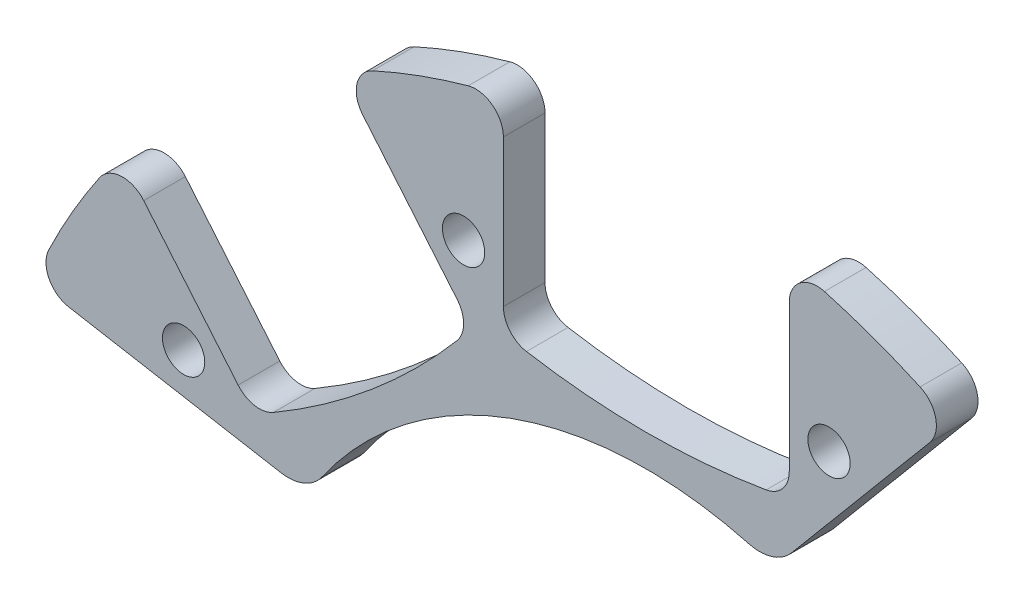
SolidWorks part; units mm, degrees
material "ﾎﾟﾘｶｰﾎﾞﾈｰﾄ(PC)高粘度"
ref_plane "正面" through (0, 0, 0) normal (0, 0, 1) x (1, 0, 0)
ref_plane "平面" through (0, 0, 0) normal (0, 1, 0) x (1, 0, 0)
ref_plane "右側面" through (0, 0, 0) normal (1, 0, 0) x (0, 0, -1)
sketch "ｽｹｯﾁ1" plane through (0, 0, 0) normal (0, 0, 1) x (1, 0, 0)
  circle A0 centre (0, 0) radius 47.75
  dimension "D1" = 95.5
extrude "ﾎﾞｽ - 押し出し1" add sketch "ｽｹｯﾁ1" along normal blind 3
sketch "ｽｹｯﾁ2" plane through (0, 0, 3) normal (0, 0, 1) x (1, 0, 0)
  line L0 (-10.3, 46.6259) -> (-10.3, 42.705)
  line L1 (10.3, 46.6259) -> (10.3, 42.705)
  line L2 (0, 47.75) -> (0, -47.75) construction
  line L3 (-10.3, 39.655) -> (-10.3, 31.8257)
  line L4 (12.9, 39.655) -> (10.3, 39.655)
  line L5 (12.9, 39.655) -> (12.9, 42.705)
  line L6 (12.9, 42.705) -> (10.3, 42.705)
  line L7 (-12.9, 39.655) -> (-12.9, 42.705)
  line L8 (12.9, 39.655) -> (-12.9, 42.705) construction
  line L9 (12.9, 42.705) -> (-12.9, 39.655) construction
  line L10 (-10.3, 39.655) -> (-12.9, 39.655)
  line L11 (-10.3, 42.705) -> (-12.9, 42.705)
  line L12 (10.3, 39.655) -> (10.3, 31.8257)
  line L13 (0, 30.78) -> (0, 41.18) construction
  line L14 (17.5995, 36.9982) -> (12.5669, 31.0006)
  line L15 (17.5995, 36.9982) -> (15.6078, 38.6695)
  line L16 (15.6078, 38.6695) -> (17.5683, 41.0059)
  line L17 (19.56, 39.3346) -> (17.5683, 41.0059)
  line L18 (22.0803, 42.3382) -> (19.56, 39.3346)
  line L19 (37.8608, 29.0968) -> (35.3405, 26.0932)
  line L20 (37.3322, 24.422) -> (35.3405, 26.0932)
  line L21 (35.3717, 22.0855) -> (37.3322, 24.422)
  line L22 (35.3717, 22.0855) -> (33.38, 23.7568)
  line L23 (33.38, 23.7568) -> (28.3474, 17.7592)
  line L24 (37.264, 17.0295) -> (29.5536, 15.67)
  line L25 (37.264, 17.0295) -> (36.8125, 19.59)
  line L26 (36.8125, 19.59) -> (39.8162, 20.1197)
  line L27 (40.2676, 17.5592) -> (39.8162, 20.1197)
  line L28 (44.1289, 18.24) -> (40.2676, 17.5592)
  line L29 (47.7061, -2.047) -> (43.8448, -2.7279)
  line L30 (44.2963, -5.2884) -> (43.8448, -2.7279)
  line L31 (41.2926, -5.818) -> (44.2963, -5.2884)
  line L32 (41.2926, -5.818) -> (40.8411, -3.2575)
  line L33 (40.8411, -3.2575) -> (33.1308, -4.617)
  line L34 (39.4922, -10.9074) -> (32.7119, -6.9928)
  line L35 (39.4922, -10.9074) -> (40.7922, -8.6558)
  line L36 (40.7922, -8.6558) -> (43.4336, -10.1808)
  line L37 (42.1336, -12.4324) -> (43.4336, -10.1808)
  line L38 (45.5292, -14.3929) -> (42.1336, -12.4324)
  line L39 (35.2292, -32.233) -> (31.8336, -30.2726)
  line L40 (30.5336, -32.5242) -> (31.8336, -30.2726)
  line L41 (27.8922, -30.9992) -> (30.5336, -32.5242)
  line L42 (27.8922, -30.9992) -> (29.1922, -28.7476)
  line L43 (29.1922, -28.7476) -> (22.4119, -24.8329)
  line L44 (23.2416, -33.7407) -> (20.5639, -26.3836)
  line L45 (23.2416, -33.7407) -> (25.6848, -32.8515)
  line L46 (25.6848, -32.8515) -> (26.728, -35.7175)
  line L47 (24.2848, -36.6068) -> (26.728, -35.7175)
  line L48 (25.6258, -40.2912) -> (24.2848, -36.6068)
  line L49 (6.2682, -47.3368) -> (4.9271, -43.6524)
  line L50 (2.4839, -44.5416) -> (4.9271, -43.6524)
  line L51 (1.4408, -41.6756) -> (2.4839, -44.5416)
  line L52 (1.4408, -41.6756) -> (3.884, -40.7863)
  line L53 (3.884, -40.7863) -> (1.2062, -33.4292)
  line L54 (-3.884, -40.7863) -> (-1.2062, -33.4292)
  line L55 (-3.884, -40.7863) -> (-1.4408, -41.6756)
  line L56 (-1.4408, -41.6756) -> (-2.4839, -44.5416)
  line L57 (-4.9271, -43.6524) -> (-2.4839, -44.5416)
  line L58 (-6.2682, -47.3368) -> (-4.9271, -43.6524)
  line L59 (-25.6258, -40.2912) -> (-24.2848, -36.6068)
  line L60 (-26.728, -35.7175) -> (-24.2848, -36.6068)
  line L61 (-25.6848, -32.8515) -> (-26.728, -35.7175)
  line L62 (-25.6848, -32.8515) -> (-23.2416, -33.7407)
  line L63 (-23.2416, -33.7407) -> (-20.5639, -26.3836)
  line L64 (-29.1922, -28.7476) -> (-22.4119, -24.8329)
  line L65 (-29.1922, -28.7476) -> (-27.8922, -30.9992)
  line L66 (-27.8922, -30.9992) -> (-30.5336, -32.5242)
  line L67 (-31.8336, -30.2726) -> (-30.5336, -32.5242)
  line L68 (-35.2292, -32.233) -> (-31.8336, -30.2726)
  line L69 (-45.5292, -14.3929) -> (-42.1336, -12.4324)
  line L70 (-43.4336, -10.1808) -> (-42.1336, -12.4324)
  line L71 (-40.7922, -8.6558) -> (-43.4336, -10.1808)
  line L72 (-40.7922, -8.6558) -> (-39.4922, -10.9074)
  line L73 (-39.4922, -10.9074) -> (-32.7119, -6.9928)
  line L74 (-40.8411, -3.2575) -> (-33.1308, -4.617)
  line L75 (-40.8411, -3.2575) -> (-41.2926, -5.818)
  line L76 (-41.2926, -5.818) -> (-44.2963, -5.2884)
  line L77 (-43.8448, -2.7279) -> (-44.2963, -5.2884)
  line L78 (-47.7061, -2.047) -> (-43.8448, -2.7279)
  line L79 (-44.1289, 18.24) -> (-40.2676, 17.5592)
  line L80 (-39.8162, 20.1197) -> (-40.2676, 17.5592)
  line L81 (-36.8125, 19.59) -> (-39.8162, 20.1197)
  line L82 (-36.8125, 19.59) -> (-37.264, 17.0295)
  line L83 (-37.264, 17.0295) -> (-29.5536, 15.67)
  line L84 (-33.38, 23.7568) -> (-28.3474, 17.7592)
  line L85 (-33.38, 23.7568) -> (-35.3717, 22.0855)
  line L86 (-35.3717, 22.0855) -> (-37.3322, 24.422)
  line L87 (-35.3405, 26.0932) -> (-37.3322, 24.422)
  line L88 (-37.8608, 29.0968) -> (-35.3405, 26.0932)
  line L89 (-22.0803, 42.3382) -> (-19.56, 39.3346)
  line L90 (-17.5683, 41.0059) -> (-19.56, 39.3346)
  line L91 (-15.6078, 38.6695) -> (-17.5683, 41.0059)
  line L92 (-15.6078, 38.6695) -> (-17.5995, 36.9982)
  line L93 (-17.5995, 36.9982) -> (-12.5669, 31.0006)
  circle A0 centre (0, 0) radius 47.75 construction
  arc A1 (-10.3, 46.6259) -> (10.3, 46.6259) centre (0, 0) cw
  arc A2 (-10.3, 31.8257) -> (10.3, 31.8257) centre (0, 82.03) ccw
  arc A3 (12.5669, 31.0006) -> (28.3474, 17.7592) centre (52.7279, 62.8386) ccw
  arc A4 (22.0803, 42.3382) -> (37.8608, 29.0968) centre (0, 0) cw
  arc A5 (29.5536, 15.67) -> (33.1308, -4.617) centre (80.7838, 14.2444) ccw
  arc A6 (44.1289, 18.24) -> (47.7061, -2.047) centre (0, 0) cw
  arc A7 (32.7119, -6.9928) -> (22.4119, -24.8329) centre (71.0401, -41.015) ccw
  arc A8 (45.5292, -14.3929) -> (35.2292, -32.233) centre (0, 0) cw
  arc A9 (20.5639, -26.3836) -> (1.2062, -33.4292) centre (28.0559, -77.083) ccw
  arc A10 (25.6258, -40.2912) -> (6.2682, -47.3368) centre (0, 0) cw
  arc A11 (-1.2062, -33.4292) -> (-20.5639, -26.3836) centre (-28.0559, -77.083) ccw
  arc A12 (-6.2682, -47.3368) -> (-25.6258, -40.2912) centre (0, 0) cw
  arc A13 (-22.4119, -24.8329) -> (-32.7119, -6.9928) centre (-71.0401, -41.015) ccw
  arc A14 (-35.2292, -32.233) -> (-45.5292, -14.3929) centre (0, 0) cw
  arc A15 (-33.1308, -4.617) -> (-29.5536, 15.67) centre (-80.7838, 14.2444) ccw
  arc A16 (-47.7061, -2.047) -> (-44.1289, 18.24) centre (0, 0) cw
  arc A17 (-28.3474, 17.7592) -> (-12.5669, 31.0006) centre (-52.7279, 62.8386) ccw
  arc A18 (-37.8608, 29.0968) -> (-22.0803, 42.3382) centre (0, 0) cw
  point P11 (0, 41.18)
  point P139 (0, 0)
  dimension "D2" = 20.6
  dimension "D7" = 51.25
  dimension "D1" = 41.18
  dimension "D3" = 10.3
  dimension "D4" = 3.05
  dimension "D5" = 25.8
  dimension "D6" = 10.4
  dimension "D8" = 9
extrude "ｶｯﾄ - 押し出し1" cut sketch "ｽｹｯﾁ2" against normal through all
fillet "ﾌｨﾚｯﾄ2" radius 2 36 edges at (-12.5669, 31.0006, 1.5) (-28.3474, 17.7592, 1.5) (-29.5536, 15.67, 1.5) (-33.1308, -4.617, 1.5) (-32.7119, -6.9928, 1.5) (-22.4119, -24.8329, 1.5) (-20.5639, -26.3836, 1.5) (-1.2062, -33.4292, 1.5) (1.2062, -33.4292, 1.5) (20.5639, -26.3836, 1.5) (32.7119, -6.9928, 1.5) (22.4119, -24.8329, 1.5) (33.1308, -4.617, 1.5) (29.5536, 15.67, 1.5) (28.3474, 17.7592, 1.5) (12.5669, 31.0006, 1.5) (10.3, 31.8257, 1.5) (-10.3, 31.8257, 1.5) (35.2292, -32.233, 1.5) (25.6258, -40.2912, 1.5) (6.2682, -47.3368, 1.5) (-6.2682, -47.3368, 1.5) (-25.6258, -40.2912, 1.5) (-35.2292, -32.233, 1.5) (-45.5292, -14.3929, 1.5) (-47.7061, -2.047, 1.5) (-44.1289, 18.24, 1.5) (-37.8608, 29.0968, 1.5) (-22.0803, 42.3382, 1.5) (-10.3, 46.6259, 1.5) (22.0803, 42.3382, 1.5) (10.3, 46.6259, 1.5) (37.8608, 29.0968, 1.5) (44.1289, 18.24, 1.5) (47.7061, -2.047, 1.5) (45.5292, -14.3929, 1.5)
sketch "ｽｹｯﾁ3" plane through (0, 0, 3) normal (0, 0, 1) x (1, 0, 0)
  line L0 (0, 0) -> (0, -38.5) construction
  line L1 (0, 0) -> (-24.7473, -29.4927) construction
  line L2 (0, 0) -> (-37.9151, -6.6855) construction
  line L3 (0, 0) -> (-33.342, 19.25) construction
  line L4 (0, 0) -> (-13.1678, 36.1782) construction
  line L5 (0, 0) -> (13.1678, 36.1782) construction
  line L6 (0, 0) -> (33.342, 19.25) construction
  line L7 (0, 0) -> (37.9151, -6.6855) construction
  line L8 (0, 0) -> (24.7473, -29.4927) construction
  circle A2 centre (0, -38.5) radius 1.525
  circle A3 centre (0, 0) radius 38.5 construction
  circle A4 centre (-24.7473, -29.4927) radius 1.525
  circle A5 centre (0, 0) radius 38.5 construction
  circle A6 centre (-37.9151, -6.6855) radius 1.525
  circle A7 centre (0, 0) radius 38.5 construction
  circle A8 centre (-33.342, 19.25) radius 1.525
  circle A9 centre (0, 0) radius 38.5 construction
  circle A10 centre (-13.1678, 36.1782) radius 1.525
  circle A11 centre (0, 0) radius 38.5 construction
  circle A12 centre (13.1678, 36.1782) radius 1.525
  circle A13 centre (0, 0) radius 38.5 construction
  circle A14 centre (33.342, 19.25) radius 1.525
  circle A15 centre (0, 0) radius 38.5 construction
  circle A16 centre (37.9151, -6.6855) radius 1.525
  circle A17 centre (0, 0) radius 38.5 construction
  circle A18 centre (24.7473, -29.4927) radius 1.525
  circle A19 centre (0, 0) radius 38.5 construction
  point P10 (0, 0)
  point P32 (0, 0)
  dimension "D1" = 3.05
  dimension "D2" = 77
  dimension "D3" = 9
extrude "ｶｯﾄ - 押し出し2" cut sketch "ｽｹｯﾁ3" against normal through all
sketch "ｽｹｯﾁ6" plane through (0, 0, 0) normal (0, 0, -1) x (-1, 0, 0)
  circle A19 centre (0, 0) radius 28.5
  dimension "D1" = 57
extrude "ｶｯﾄ - 押し出し4" cut sketch "ｽｹｯﾁ6" against normal through all
sketch "ｽｹｯﾁ9" plane through (0, 0, 0) normal (0, 0, -1) x (-1, 0, 0)
  line L0 (-19.56, 39.3346) -> (-17.5995, 36.9982)
  line L1 (-17.5995, 36.9982) -> (-15.6078, 38.6695)
  line L2 (-15.6078, 38.6695) -> (-17.5683, 41.0059)
  line L3 (-17.5683, 41.0059) -> (-19.56, 39.3346)
  line L4 (-10.3, 39.655) -> (-12.9, 39.655)
  line L5 (-12.9, 39.655) -> (-12.9, 42.705)
  line L6 (-12.9, 42.705) -> (-10.3, 42.705)
  line L7 (-10.3, 42.705) -> (-10.3, 39.655)
  line L8 (10.3, 42.705) -> (10.3, 39.655)
  line L9 (10.3, 39.655) -> (12.9, 39.655)
  line L10 (12.9, 39.655) -> (12.9, 42.705)
  line L11 (12.9, 42.705) -> (10.3, 42.705)
  line L12 (17.5995, 36.9982) -> (15.6078, 38.6695)
  line L13 (15.6078, 38.6695) -> (17.5683, 41.0059)
  line L14 (17.5683, 41.0059) -> (19.56, 39.3346)
  line L15 (19.56, 39.3346) -> (17.5995, 36.9982)
  line L16 (33.38, 23.7568) -> (35.3717, 22.0855)
  line L17 (35.3717, 22.0855) -> (37.3322, 24.422)
  line L18 (37.3322, 24.422) -> (35.3405, 26.0932)
  line L19 (35.3405, 26.0932) -> (33.38, 23.7568)
  line L20 (36.8125, 19.59) -> (37.264, 17.0295)
  line L21 (37.264, 17.0295) -> (40.2676, 17.5592)
  line L22 (40.2676, 17.5592) -> (39.8162, 20.1197)
  line L23 (39.8162, 20.1197) -> (36.8125, 19.59)
extrude "ﾎﾞｽ - 押し出し3" add sketch "ｽｹｯﾁ9" against normal up to surface (3 mm away) up to face at (-28.5, 0, 3)
sketch "ｽｹｯﾁ10" plane through (0, 0, 0) normal (0, 0, -1) x (-1, 0, 0)
  line L0 (-22.9026, 43.3182) -> (4.0678, 11.1762)
  line L1 (4.0678, 11.1762) -> (45.3889, 18.4622)
  line L2 (-20.4345, 40.3769) -> (-13.6331, 32.2713) construction
  line L3 (31.1871, 15.958) -> (41.6075, 17.7954) construction
  arc A0 (-22.9026, 43.3182) -> (45.3889, 18.4622) centre (0, 0) ccw
  dimension "D1" = 49
extrude "ｶｯﾄ - 押し出し6" cut sketch "ｽｹｯﾁ10" against normal through all
fillet "ﾌｨﾚｯﾄ4" radius 3 2 edges at (-24.3814, 14.758, 1.5) (9.191, 26.9773, 1.5)
